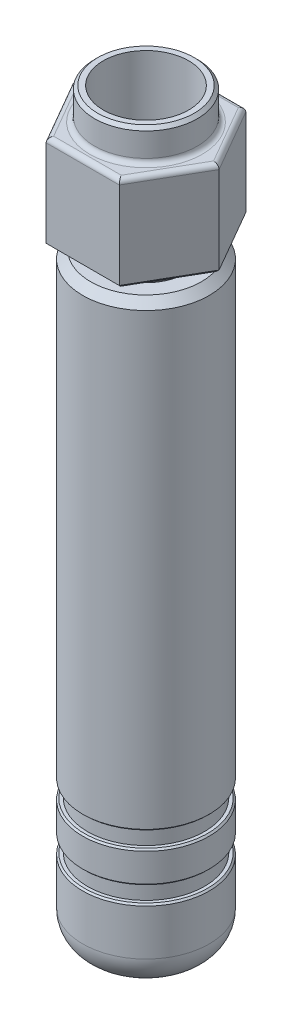
SolidWorks part; units mm, degrees
ref_plane "前视基准面" through (0, 0, 0) normal (0, 0, 1) x (1, 0, 0)
ref_plane "上视基准面" through (0, 0, 0) normal (0, 1, 0) x (1, 0, 0)
ref_plane "右视基准面" through (0, 0, 0) normal (1, 0, 0) x (0, 0, -1)
sketch "草图1" plane through (0, 0, 0) normal (0, 1, 0) x (1, 0, 0)
  circle A0 centre (0, 0) radius 2.85
  dimension "D1" = 5.7
extrude "凸台-拉伸1" add sketch "草图1" along normal blind 1
sketch "草图2" plane through (0, 1, 0) normal (0, 1, 0) x (1, 0, 0)
  line L1 (4.6188, 0) -> (2.3094, 4)
  line L2 (2.3094, 4) -> (-2.3094, 4)
  line L3 (-2.3094, 4) -> (-4.6188, 0)
  line L4 (-4.6188, 0) -> (-2.3094, -4)
  line L5 (-2.3094, -4) -> (2.3094, -4)
  line L6 (2.3094, -4) -> (4.6188, 0)
  circle A0 centre (0, 0) radius 4 construction
  dimension "D1" = 8
extrude "凸台-拉伸2" add sketch "草图2" along normal blind 6
sketch "草图3" plane through (0, 7, 0) normal (0, 1, 0) x (1, 0, 0)
  circle A0 centre (0, 0) radius 3.25
  dimension "D1" = 6.5
extrude "凸台-拉伸3" add sketch "草图3" along normal blind 2
chamfer "倒角3" distance 0.2 angle 45 7 edges at (3.4641, 1, -2) (0, 1, -4) (-3.4641, 1, -2) (-3.4641, 1, 2) (0, 1, 4) (3.4641, 1, 2) (0, 1, 2.85)
fillet "圆角2" radius 0.3 7 edges at (0, 7, 4) (-3.4641, 7, 2) (-3.4641, 7, -2) (0, 7, -4) (3.4641, 7, -2) (3.4641, 7, 2) (0, 7, 3.25)
chamfer "倒角4" distance 0.2 angle 45 1 edges at (0, 9, 3.25)
chamfer "倒角5" distance 0.3 angle 45 1 edges at (0, 0, 2.85)
sketch "草图5" plane through (0, 9, 0) normal (0, 1, 0) x (1, 0, 0)
  circle A0 centre (0, 0) radius 2.7
  dimension "D1" = 5.4
extrude "切除-拉伸1" cut sketch "草图5" against normal blind 5
sketch "草图6" plane through (0, 0, 0) normal (0, -1, 0) x (1, 0, 0)
  circle A0 centre (0, 0) radius 4
  dimension "D1" = 8
extrude "凸台-拉伸4" add sketch "草图6" along normal blind 38
fillet "圆角3" radius 2 1 edges at (0, -38, -4)
chamfer "倒角6" distance 0.5 angle 45 1 edges at (0, 0, -4)
sketch "草图7" plane through (0, 0, 0) normal (1, 0, 0) x (0, 0, -1)
  line L0 (-2, -38) -> (2, -38) construction
  line L1 (-7.7, -32) -> (-3.7, -32)
  line L2 (-7.7, -32) -> (-7.7, -33)
  line L3 (-7.7, -33) -> (-3.7, -33)
  line L4 (-3.7, -32) -> (-3.7, -33)
  line L5 (-7.7, -29) -> (-3.7, -29)
  line L6 (-7.7, -29) -> (-7.7, -30)
  line L7 (-7.7, -30) -> (-3.7, -30)
  line L8 (-3.7, -29) -> (-3.7, -30)
  line L9 (0, 0) -> (0, -44.5871) construction
  dimension "D1" = 1
  dimension "D2" = 4
  dimension "D3" = 3.7
  dimension "D4" = 3
  dimension "D5" = 5
revolve "切除-旋转1" cut sketch "草图7" angle 360 about L9
chamfer "倒角7" distance 0.1 angle 45 4 edges at (0, -33, -4) (0, -32, 4) (0, -30, -4) (0, -29, 4)
